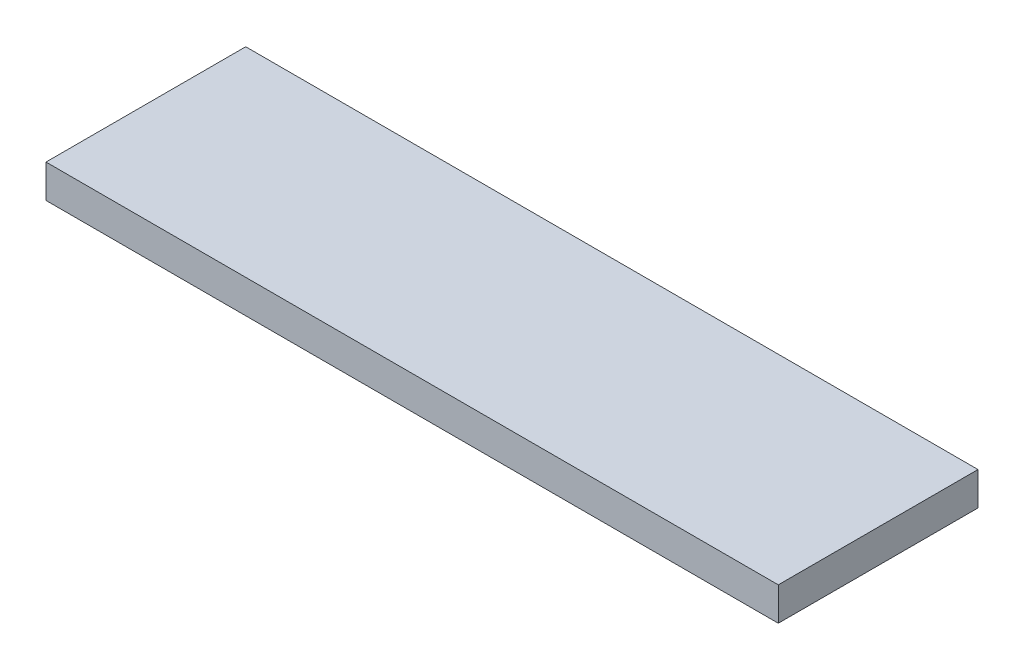
SolidWorks part; units mm, degrees
ref_plane "Front Plane" through (0, 0, 0) normal (0, 0, 1) x (1, 0, 0)
ref_plane "Top Plane" through (0, 0, 0) normal (0, 1, 0) x (1, 0, 0)
ref_plane "Right Plane" through (0, 0, 0) normal (1, 0, 0) x (0, 0, -1)
sketch "Sketch1" plane through (0, 0, 0) normal (0, 1, 0) x (1, 0, 0)
  line L1 (-550, -150) -> (550, -150)
  line L2 (-550, -150) -> (-550, 150)
  line L3 (-550, 150) -> (550, 150)
  line L4 (550, -150) -> (550, 150)
  line L5 (0, 150) -> (0, -150) construction
  line L6 (-550, 0) -> (550, 0) construction
  point P0 (0, 0)
  dimension "D1" = 1100
  dimension "D2" = 300
extrude "Boss-Extrude1" add sketch "Sketch1" along normal blind 50
